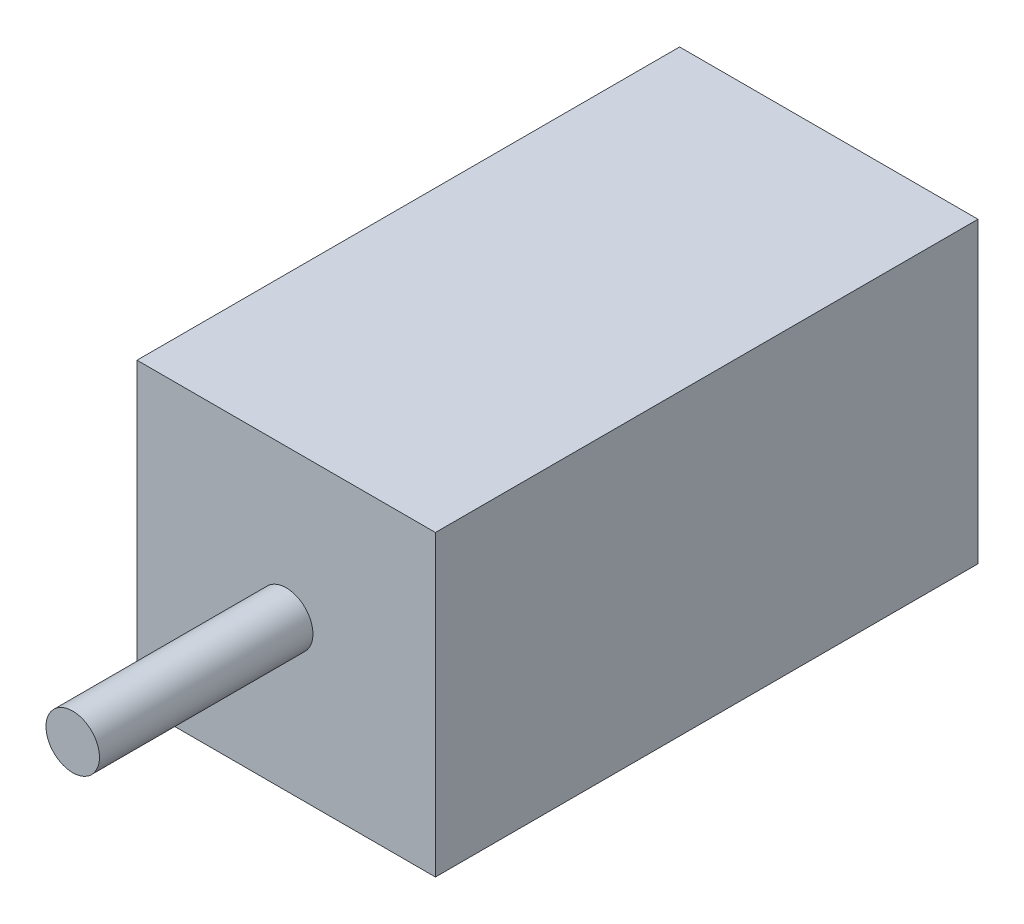
SolidWorks part; units mm, degrees
ref_plane "Front Plane" through (0, 0, 0) normal (0, 0, 1) x (1, 0, 0)
ref_plane "Top Plane" through (0, 0, 0) normal (0, 1, 0) x (1, 0, 0)
ref_plane "Right Plane" through (0, 0, 0) normal (1, 0, 0) x (0, 0, -1)
sketch "Sketch1" plane through (0, 0, 0) normal (0, 0, 1) x (1, 0, 0)
  line L1 (-13.97, -13.97) -> (13.97, -13.97)
  line L2 (-13.97, -13.97) -> (-13.97, 13.97)
  line L3 (-13.97, 13.97) -> (13.97, 13.97)
  line L4 (13.97, -13.97) -> (13.97, 13.97)
  line L5 (-13.97, -13.97) -> (13.97, 13.97) construction
  line L6 (-13.97, 13.97) -> (13.97, -13.97) construction
  point P0 (0, 0)
  dimension "D1" = 27.94
  dimension "D2" = 27.94
extrude "Boss-Extrude1" add sketch "Sketch1" along normal blind 50.8
sketch "Sketch2" plane through (0, 0, 50.8) normal (0, 0, 1) x (1, 0, 0)
  circle A0 centre (0, 0) radius 2.5019
  dimension "D1" = 5.0038
extrude "Boss-Extrude2" add sketch "Sketch2" along normal blind 19.9898
